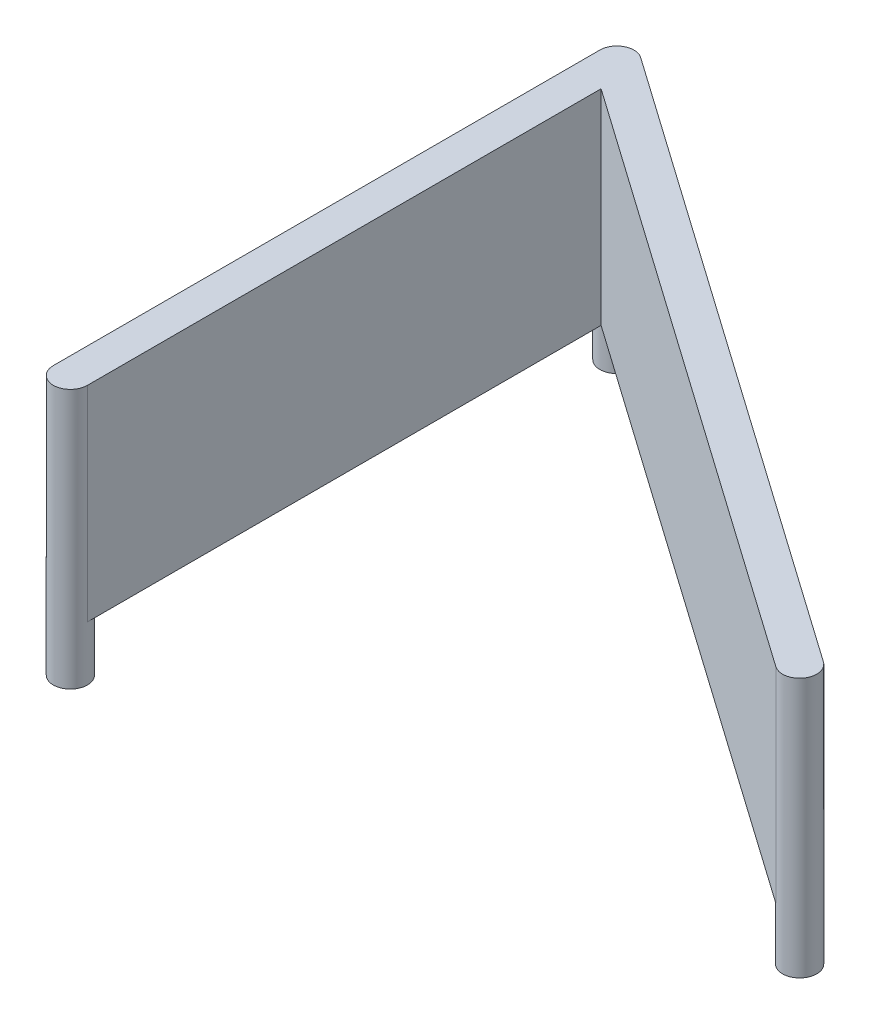
SolidWorks part; units mm, degrees
ref_plane "Front Plane" through (0, 0, 0) normal (0, 0, 1) x (1, 0, 0)
ref_plane "Top Plane" through (0, 0, 0) normal (0, 1, 0) x (1, 0, 0)
ref_plane "Right Plane" through (0, 0, 0) normal (1, 0, 0) x (0, 0, -1)
sketch "Sketch1" plane through (0, 0, 0) normal (0, 1, 0) x (1, 0, 0)
  line L0 (0, 0) -> (0, 101.6) construction
  line L1 (-3.175, 0) -> (-3.175, 101.6)
  line L2 (3.175, 0) -> (3.175, 95.4883)
  line L3 (0, 101.6) -> (114.3, 21.2781) construction
  line L4 (1.8255, 104.1977) -> (116.1255, 23.8759)
  line L7 (3.175, 95.4883) -> (112.4745, 18.6804)
  arc A0 (-3.175, 0) -> (3.175, 0) centre (0, 0) ccw
  arc A1 (1.8255, 104.1977) -> (-3.175, 101.6) centre (0, 101.6) ccw
  arc A3 (112.4745, 18.6804) -> (116.1255, 23.8759) centre (114.3, 21.2781) ccw
  point P3 (0, 50.8)
  point P8 (57.15, 61.4391)
  point P15 (0, 0)
  dimension "D2" = 6.35
  dimension "D3" = 101.6
  dimension "D4" = 139.7
  dimension "D5" = 114.3
extrude "Boss-Extrude1" add sketch "Sketch1" along normal blind 38.1
sketch "Sketch2" plane through (0, 0, 0) normal (0, -1, 0) x (-1, 0, 0)
  circle A0 centre (0, 0) radius 3.175
  circle A1 centre (0, 101.6) radius 3.175
  circle A2 centre (-114.3, 21.2781) radius 3.175
extrude "Boss-Extrude2" add sketch "Sketch2" along normal blind 10.16
